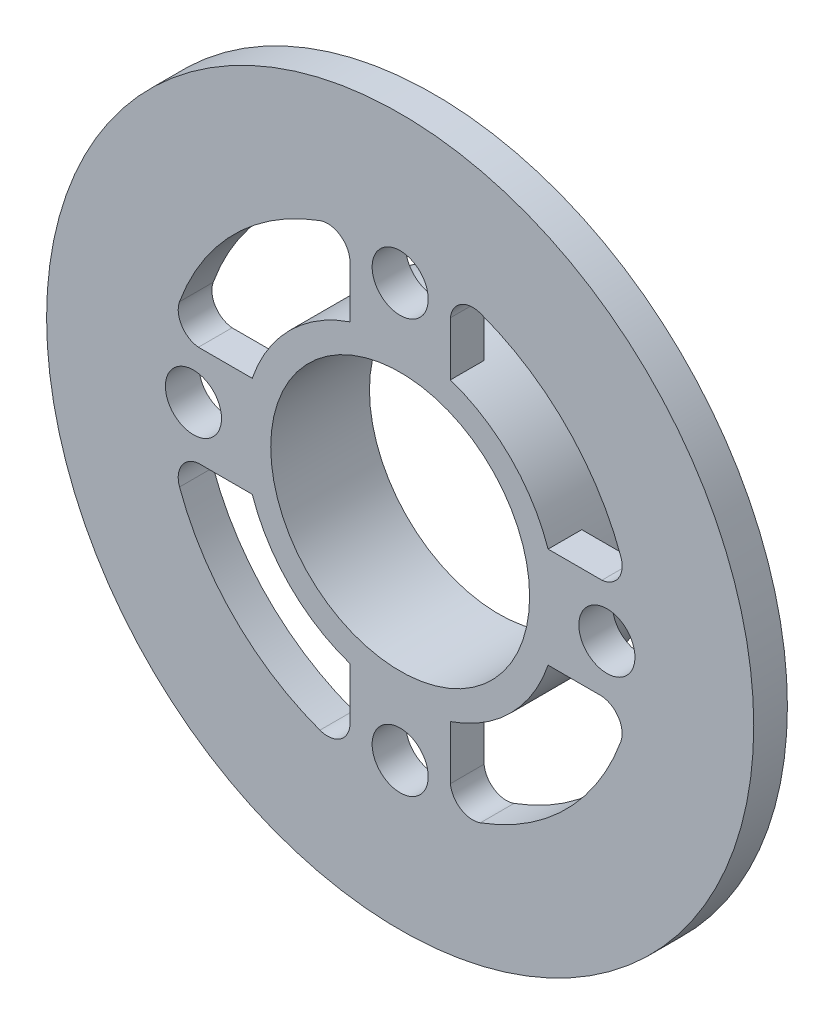
SolidWorks part; units mm, degrees
ref_plane "Front Plane" through (0, 0, 0) normal (0, 0, 1) x (1, 0, 0)
ref_plane "Top Plane" through (0, 0, 0) normal (0, 1, 0) x (1, 0, 0)
ref_plane "Right Plane" through (0, 0, 0) normal (1, 0, 0) x (0, 0, -1)
sketch "Model" plane through (0, 0, 0) normal (0, 0, 1) x (1, 0, 0)
  line L0 (17.5, -10.1036) -> (17.5, 10.1036)
  line L1 (17.5, 10.1036) -> (0, 20.2073)
  line L2 (0, 20.2073) -> (-17.5, 10.1036)
  line L3 (-17.5, -10.1036) -> (0, -20.2073)
  line L4 (0, -20.2073) -> (17.5, -10.1036)
  line L5 (-17.5, 10.1036) -> (-17.5, -10.1036)
  circle A0 centre (-38.1051, -22) radius 4.1
  circle A1 centre (38.1051, -22) radius 4.1
  circle A2 centre (0, 44) radius 4.1
  circle A3 centre (0, 0) radius 52.5
sketch "Sketch2" plane through (0, 0, 0) normal (0, 0, 1) x (1, 0, 0)
  line L0 (0, 20.2073) -> (-17.5, 10.1036)
  line L1 (-17.5, 10.1036) -> (-17.5, -10.1036)
  line L2 (-17.5, -10.1036) -> (0, -20.2073)
  line L3 (0, -20.2073) -> (17.5, -10.1036)
  line L4 (17.5, -10.1036) -> (17.5, 10.1036)
  line L5 (17.5, 10.1036) -> (0, 20.2073)
  circle A0 centre (0, 0) radius 52.5
  circle A1 centre (0, 44) radius 4.1
  circle A2 centre (38.1051, -22) radius 4.1
  circle A3 centre (-38.1051, -22) radius 4.1
extrude "Boss-Extrude1" add sketch "Sketch2" along normal blind 3
sketch "Sketch3" plane through (0, 0, 0) normal (0, 0, -1) x (-1, 0, 0)
  circle A0 centre (0, 0) radius 20.925
  dimension "D1" = 41.85
extrude "Cut-Extrude1" cut sketch "Sketch3" against normal blind 9
sketch "Sketch4" plane through (0, 0, 0) normal (0, 0, -1) x (-1, 0, 0)
  line L0 (0, 20.925) -> (0, 18.425) construction
  line L1 (-20.925, 0) -> (-18.425, 0) construction
  line L2 (0, 20.925) -> (0, -20.925) construction
  circle A1 centre (0, 18.425) radius 2.5
  circle A2 centre (0, -18.425) radius 2.5
  circle A3 centre (-18.425, 0) radius 2.5
  circle A4 centre (18.425, 0) radius 2.5
  circle A5 centre (0, 18.425) radius 4.5
  circle A6 centre (-18.425, 0) radius 4.5
  circle A7 centre (0, -18.425) radius 4.5
  circle A8 centre (18.425, 0) radius 4.5
  dimension "D1" = 2.5
  dimension "D2" = 2.5
  dimension "D3" = 2
extrude "Boss-Extrude2" add sketch "Sketch4" against normal up to surface (3 mm away) up to face at (20.925, 0, 3)
fillet "Fillet1" radius 2 8 edges at (-3.9693, -20.5451, 1.5) (3.9693, -20.5451, 1.5) (-20.5451, 3.9693, 1.5) (-20.5451, -3.9693, 1.5) (20.5451, -3.9693, 1.5) (20.5451, 3.9693, 1.5) (3.9693, 20.5451, 1.5) (-3.9693, 20.5451, 1.5)
sketch "Sketch5" plane through (0, 0, 0) normal (0, 0, -1) x (-1, 0, 0)
  circle A0 centre (0, 0) radius 31.5158
  circle A1 centre (0, 0) radius 52.5
extrude "Cut-Extrude2" cut sketch "Sketch5" against normal blind 11.8
sketch "Sketch6" plane through (0, 0, 0) normal (0, 0, -1) x (-1, 0, 0)
  circle A0 centre (0, 0) radius 13.925
  circle A1 centre (0, 0) radius 11.5378
extrude "Boss-Extrude3" add sketch "Sketch6" along normal blind 5.8 and the other way up to surface (3 mm away) separate body other way up to face at (-15.925, 0, 3)
sketch "Sketch7" plane through (0, 0, 3) normal (0, 0, 1) x (1, 0, 0)
  line L0 (17.9821, 4.4782) -> (13.1853, 4.4782)
  line L1 (17.9821, -4.4782) -> (13.1853, -4.4782)
  line L2 (13.1853, 4.4782) -> (13.1853, -4.4782)
  line L3 (17.9821, 4.4782) -> (17.5, 3.1927)
  line L4 (17.5, -10.1036) -> (17.5, 10.1036) construction
  line L5 (17.5, 3.1927) -> (16.0604, 2.3152)
  line L6 (16.0604, 2.3152) -> (15.1031, 0.7836)
  line L7 (15.1031, 0.7836) -> (15.1031, -1.8011)
  line L8 (15.1031, -1.8011) -> (16.4598, -2.649)
  line L9 (16.4598, -2.649) -> (17.9821, -3.6004)
  line L10 (17.9821, -3.6004) -> (17.9821, -4.4782)
  line L11 (4.4782, -17.9821) -> (4.4782, -13.1853)
  line L12 (4.4782, -13.1853) -> (-4.4782, -13.1853)
  line L13 (-4.4782, -17.9821) -> (-4.4782, -13.1853)
  line L14 (-3.6004, -17.9821) -> (-4.4782, -17.9821)
  line L15 (-2.649, -16.4598) -> (-3.6004, -17.9821)
  line L16 (-1.8011, -15.1031) -> (-2.649, -16.4598)
  line L17 (2.3152, -16.0604) -> (0.7836, -15.1031)
  line L18 (0.7836, -15.1031) -> (-1.8011, -15.1031)
  line L19 (3.1927, -17.5) -> (2.3152, -16.0604)
  line L20 (4.4782, -17.9821) -> (3.1927, -17.5)
  line L21 (-17.9821, -4.4782) -> (-13.1853, -4.4782)
  line L22 (-13.1853, -4.4782) -> (-13.1853, 4.4782)
  line L23 (-17.9821, 4.4782) -> (-13.1853, 4.4782)
  line L24 (-17.9821, 3.6004) -> (-17.9821, 4.4782)
  line L25 (-16.4598, 2.649) -> (-17.9821, 3.6004)
  line L26 (-15.1031, 1.8011) -> (-16.4598, 2.649)
  line L27 (-16.0604, -2.3152) -> (-15.1031, -0.7836)
  line L28 (-15.1031, -0.7836) -> (-15.1031, 1.8011)
  line L29 (-17.5, -3.1927) -> (-16.0604, -2.3152)
  line L30 (-17.9821, -4.4782) -> (-17.5, -3.1927)
  line L31 (-4.4782, 17.9821) -> (-4.4782, 13.1853)
  line L32 (-4.4782, 13.1853) -> (4.4782, 13.1853)
  line L33 (4.4782, 17.9821) -> (4.4782, 13.1853)
  line L34 (3.6004, 17.9821) -> (4.4782, 17.9821)
  line L35 (2.649, 16.4598) -> (3.6004, 17.9821)
  line L36 (1.8011, 15.1031) -> (2.649, 16.4598)
  line L37 (-2.3152, 16.0604) -> (-0.7836, 15.1031)
  line L38 (-0.7836, 15.1031) -> (1.8011, 15.1031)
  line L39 (-3.1927, 17.5) -> (-2.3152, 16.0604)
  line L40 (-4.4782, 17.9821) -> (-3.1927, 17.5)
  circle A0 centre (0, 0) radius 13.925 construction
  point P8 (0, 0)
  point P25 (0, 0)
  point P36 (0, 0)
  point P47 (0, 0)
  point P54 (0, 0)
  dimension "D1" = 4
extrude "Boss-Extrude4" add sketch "Sketch7" against normal up to surface (3 mm away) up to face at (-15.925, 0, 0)
